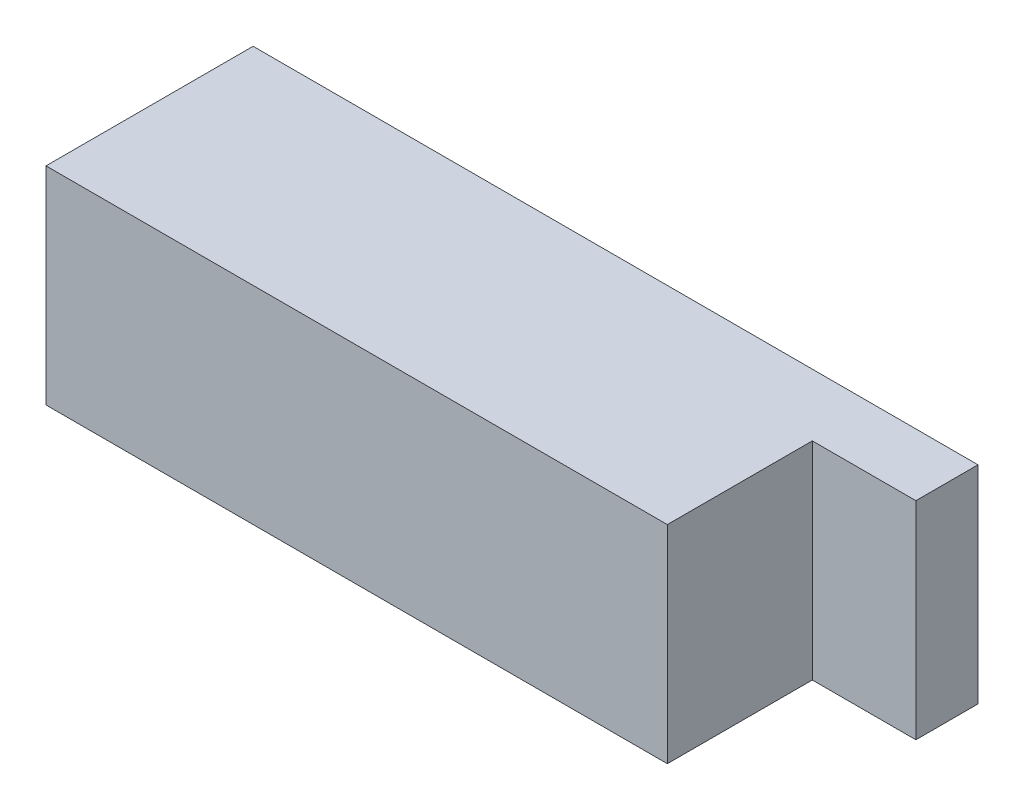
SolidWorks part; units mm, degrees
material "Plain Carbon Steel"
ref_plane "Front Plane" through (0, 0, 0) normal (0, 0, 1) x (1, 0, 0)
ref_plane "Top Plane" through (0, 0, 0) normal (0, 1, 0) x (1, 0, 0)
ref_plane "Right Plane" through (0, 0, 0) normal (1, 0, 0) x (0, 0, -1)
sketch "Sketch1" plane through (0, 0, 0) normal (0, 1, 0) x (1, 0, 0)
  line L1 (-17.5, -5) -> (17.5, -5)
  line L2 (-17.5, -5) -> (-17.5, 5)
  line L3 (-17.5, 5) -> (17.5, 5)
  line L4 (17.5, -5) -> (17.5, 5)
  line L5 (-17.5, -5) -> (17.5, 5) construction
  line L6 (-17.5, 5) -> (17.5, -5) construction
  point P0 (0, 0)
  dimension "D1" = 35
  dimension "D2" = 10
extrude "Boss-Extrude1" add sketch "Sketch1" along normal blind 10
sketch "Sketch3" plane through (0, 10, 0) normal (0, 1, 0) x (1, 0, 0)
  line L0 (17.5, 5) -> (-17.5, 5) construction
  line L1 (17.5, -5) -> (12.5, -5)
  line L2 (17.5, -5) -> (17.5, 2)
  line L3 (17.5, 2) -> (12.5, 2)
  line L4 (12.5, -5) -> (12.5, 2)
  dimension "D1" = 5
  dimension "D2" = 3
extrude "Cut-Extrude2" cut sketch "Sketch3" against normal up to next
